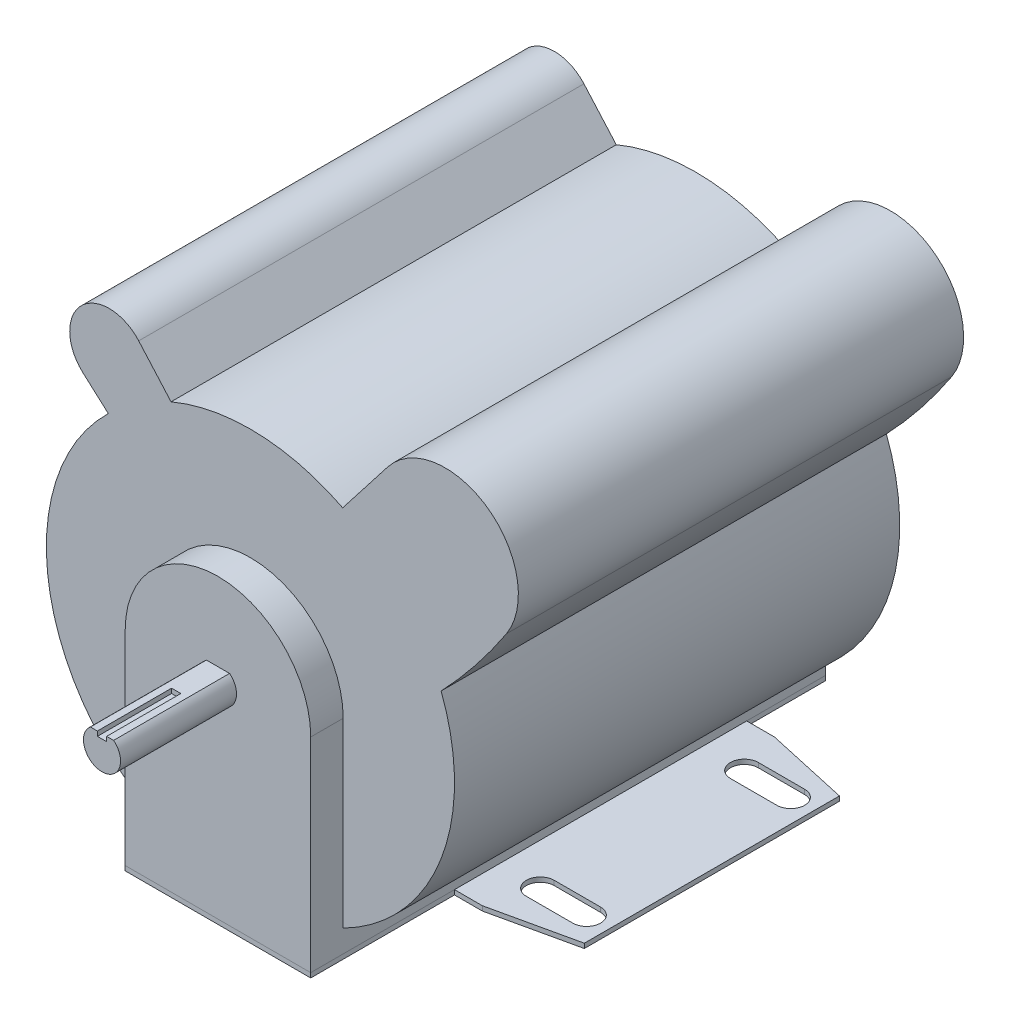
SolidWorks part; units mm, degrees
ref_plane "Front Plane" through (0, 0, 0) normal (0, 0, 1) x (1, 0, 0)
ref_plane "Top Plane" through (0, 0, 0) normal (0, 1, 0) x (1, 0, 0)
ref_plane "Right Plane" through (0, 0, 0) normal (1, 0, 0) x (0, 0, -1)
sketch "Sketch1" plane through (0, 0, 0) normal (0, 0, 1) x (1, 0, 0)
  line L0 (-3.9688, 4.957) -> (3.9688, 4.957)
  arc A0 (-3.9688, 4.957) -> (3.9688, 4.957) centre (0, 0) ccw
  dimension "D1" = 6.35
  dimension "D2" = 7.9375
extrude "Boss-Extrude1" add sketch "Sketch1" along normal blind 50.8
sketch "Sketch2" plane through (0, 0, 0) normal (0, 0, -1) x (-1, 0, 0)
  circle A0 centre (0, 0) radius 69.85
  dimension "D1" = 139.7
extrude "Boss-Extrude2" add sketch "Sketch2" along normal blind 152.4
sketch "Sketch3" plane through (0, 0, 0) normal (0, 0, 1) x (1, 0, 0)
  line L0 (-31.75, 0) -> (-31.75, -69.85)
  line L1 (-31.75, -69.85) -> (31.75, -69.85)
  line L2 (31.75, -69.85) -> (31.75, 0)
  arc A0 (31.75, 0) -> (-31.75, 0) centre (0, 0) ccw
  dimension "D1" = 63.5
extrude "Boss-Extrude3" add sketch "Sketch3" along normal blind 11.1125 and the other way offset from surface (165.1 mm away) 12.7 other way up to face at (-69.85, 0, -152.4)
sketch "Sketch4" plane through (0, -69.85, 0) normal (0, -1, 0) x (1, 0, 0)
  line L2 (-69.85, -44.45) -> (-69.85, -131.7625)
  line L4 (69.85, -44.45) -> (69.85, -131.7625)
  line L5 (0, -44.45) -> (0, 0) construction
  line L6 (-69.85, -44.45) -> (-41.275, -38.1)
  line L7 (-41.275, -38.1) -> (41.275, -38.1)
  line L8 (41.275, -38.1) -> (69.85, -44.45)
  line L9 (-69.85, -131.7625) -> (-41.275, -138.1125)
  line L10 (-41.275, -138.1125) -> (41.275, -138.1125)
  line L11 (41.275, -138.1125) -> (69.85, -131.7625)
  line L12 (-41.275, -38.1) -> (-41.275, -138.1125) construction
  line L13 (41.275, -38.1) -> (41.275, -138.1125) construction
  line L14 (69.85, -131.7625) -> (-69.85, -131.7625) construction
  line L15 (-69.85, -44.45) -> (69.85, -44.45) construction
  line L16 (6.35, 50.8) -> (-6.35, 50.8) construction
  line L17 (-31.75, 11.1125) -> (-31.75, -38.1)
  line L18 (-31.75, 11.1125) -> (31.75, 11.1125)
  line L19 (31.75, 11.1125) -> (31.75, -38.1)
  point P10 (0, -44.45)
  line M5 (-31.75, -165.1) -> (31.75, -165.1)
  line M6 (-31.75, -165.1) -> (31.75, -165.1)
  line M7 (31.75, -165.1) -> (31.75, 11.1125)
  line M8 (31.75, 11.1125) -> (-31.75, 11.1125)
  line M9 (-31.75, 11.1125) -> (-31.75, -165.1)
  dimension "D1" = 139.7
  dimension "D2" = 87.3125
  dimension "D3" = 6.35
  dimension "D4" = 6.35
  dimension "D5" = 28.575
  dimension "D6" = 28.575
  dimension "D7" = 88.9
extrude "Boss-Extrude4" add sketch "Sketch4" along normal blind 1.5875 separate body contours L19 L17 L7 M6 M5 | L10 L11 L4 L8 L7 L6 L2 L9 | M9 M5 M6 M7 M8
sketch "Sketch5" plane through (0, -71.4375, 0) normal (0, -1, 0) x (1, 0, 0)
  line L0 (-61.9125, -53.1813) -> (-46.0375, -53.1812) construction
  line L1 (-61.9125, -48.4187) -> (-46.0375, -48.4187)
  line L2 (-61.9125, -57.9437) -> (-46.0375, -57.9437)
  line L6 (-61.9125, -127.7937) -> (-46.0375, -127.7937)
  line L7 (-61.9125, -118.2687) -> (-46.0375, -118.2687)
  line L8 (-61.9125, -123.0312) -> (-46.0375, -123.0312) construction
  line L9 (-53.975, -57.9437) -> (-53.975, -118.2687) construction
  line L10 (-53.975, -88.1062) -> (-69.85, -88.1063) construction
  line L12 (-69.85, -44.45) -> (-69.85, -131.7625) construction
  arc A0 (-61.9125, -48.4187) -> (-61.9125, -57.9437) centre (-61.9125, -53.1813) ccw
  arc A1 (-46.0375, -57.9437) -> (-46.0375, -48.4187) centre (-46.0375, -53.1812) ccw
  arc A2 (-61.9125, -118.2687) -> (-61.9125, -127.7937) centre (-61.9125, -123.0312) ccw
  arc A3 (-46.0375, -127.7937) -> (-46.0375, -118.2687) centre (-46.0375, -123.0312) ccw
  point P2 (-53.975, -53.1812)
  point P7 (-66.675, -53.1812)
  point P15 (-53.975, -123.0312)
  dimension "D2" = 25.4
  dimension "D3" = 3.175
  dimension "D1" = 9.525
  dimension "D6" = 60.325
  dimension "D5" = 2
extrude "Cut-Extrude1" cut sketch "Sketch5" against normal up to next (1.5875 mm away)
mirror "Mirror1" about plane through (0, 0, 0) normal (1, 0, 0) of "Cut-Extrude1"
sketch "Sketch6" plane through (0, 0, 0) normal (0, 0, 1) x (1, 0, 0)
  line L0 (-57.3395, 57.8775) -> (-43.2134, 45.273)
  line L1 (-38.243, 76.8798) -> (-24.9815, 61.8686)
  line L2 (-43.2134, 45.273) -> (-24.9815, 61.8686)
  line L3 (22.2964, 50.3644) -> (46.9442, 82.0543)
  line L4 (0, 0) -> (66.6936, 66.6936) construction
  line L5 (66.6936, 66.6936) -> (66.6936, -64.9292) construction
  arc A0 (-38.243, 76.8798) -> (-57.3395, 57.8775) centre (-48.3557, 67.9459) ccw
  arc A2 (46.9442, 82.0543) -> (87.6031, 52.9537) centre (66.6936, 66.6936) cw
  arc A3 (87.6031, 52.9537) -> (58.7653, 18.3351) centre (-79.0853, 162.4875) cw
  arc A4 (58.7653, 18.3351) -> (22.2964, 50.3644) centre (-35.1153, -51.7817) ccw
  circle A5 centre (66.6936, 66.6936) radius 25.0199 construction
  dimension "D1" = 26.9875
  dimension "D2" = 50
  dimension "D3" = 45
extrude "Boss-Extrude5" add sketch "Sketch6" against normal up to surface (152.4 mm away) up to face at (0, 9.8457, -152.4)
sketch "Sketch7" plane through (0, 0, 50.8) normal (0, 0, 1) x (1, 0, 0)
  line L0 (3.9688, 4.957) -> (-3.9688, 4.957) construction
  line L1 (-1.5875, 4.957) -> (1.5875, 4.957)
  line L2 (-1.5875, 4.957) -> (-1.5875, 3.3695)
  line L3 (-1.5875, 3.3695) -> (1.5875, 3.3695)
  line L4 (1.5875, 4.957) -> (1.5875, 3.3695)
  line L5 (0, 0) -> (0, 3.3695) construction
  dimension "D1" = 1.5875
  dimension "D2" = 3.175
extrude "Cut-Extrude2" cut sketch "Sketch7" against normal blind 25.4
